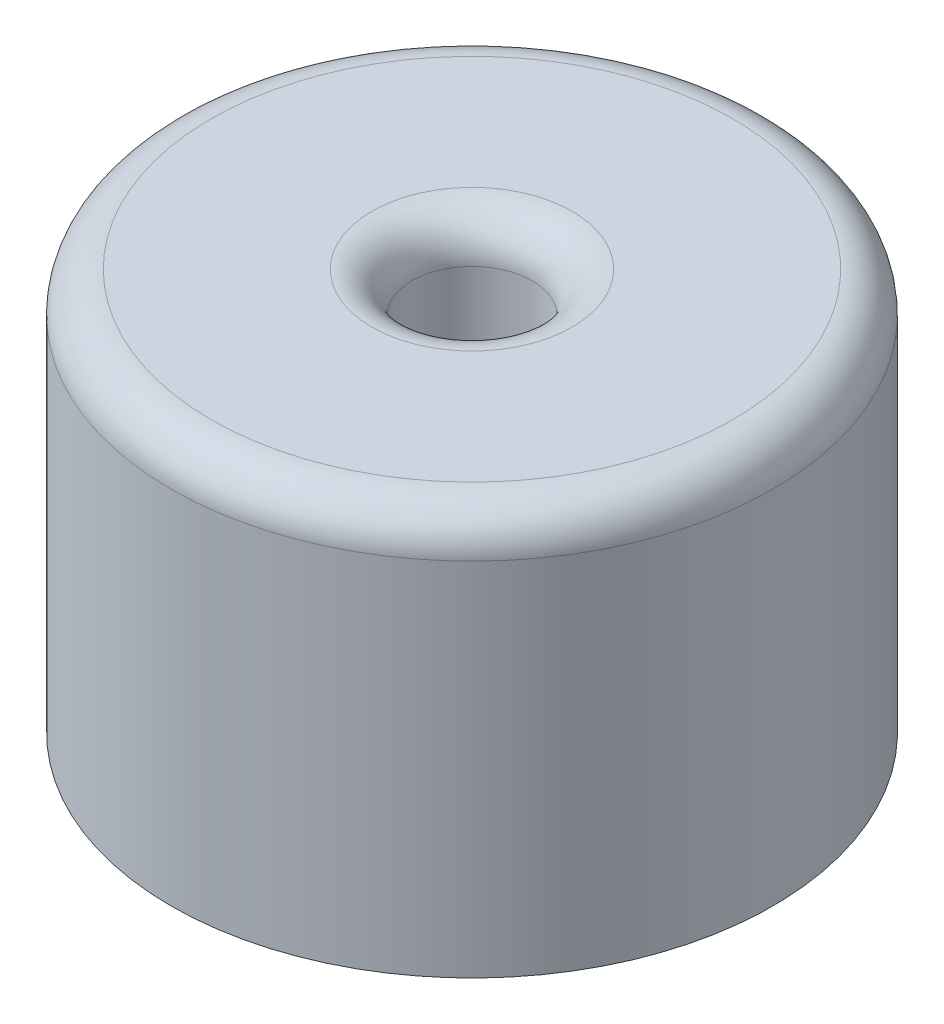
SolidWorks part; units mm, degrees
ref_plane "Front Plane" through (0, 0, 0) normal (0, 0, 1) x (1, 0, 0)
ref_plane "Top Plane" through (0, 0, 0) normal (0, 1, 0) x (1, 0, 0)
ref_plane "Right Plane" through (0, 0, 0) normal (1, 0, 0) x (0, 0, -1)
sketch "Sketch3" plane through (0, 0, 0) normal (0, 1, 0) x (1, 0, 0)
  circle A0 centre (0, 0) radius 19.05
extrude "Boss-Extrude1" add sketch "Sketch3" along normal blind 25.4
sketch "Sketch4" plane through (0, 25.4, 0) normal (0, 1, 0) x (1, 0, 0)
  circle A0 centre (0, 0) radius 3.81
extrude "Cut-Extrude1" cut sketch "Sketch4" against normal blind 25.4 contours A0
fillet "Fillet1" radius 2.54 3 edges at (0, 25.4, 19.05) (0, 25.4, 3.81) (0, 0, 3.81)
